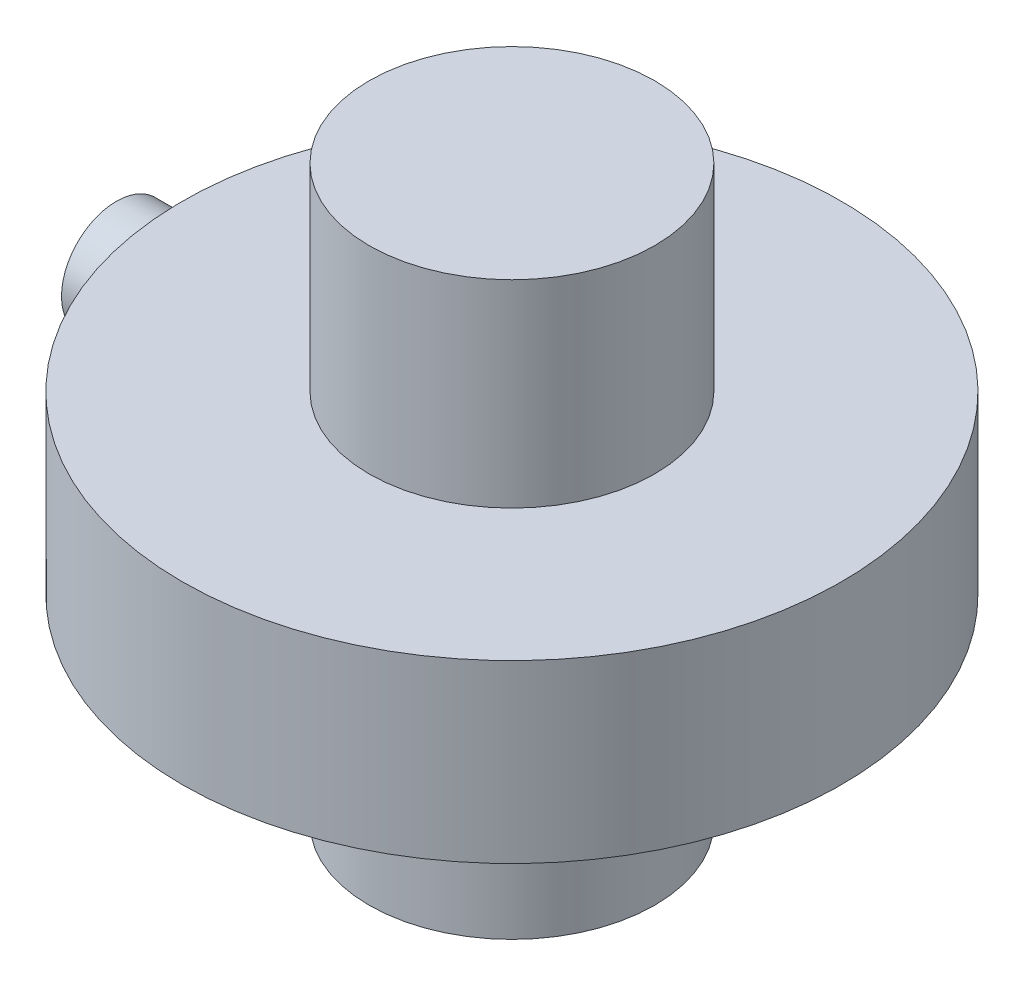
SolidWorks part; units mm, degrees
ref_plane "Front Plane" through (0, 0, 0) normal (0, 0, 1) x (1, 0, 0)
ref_plane "Top Plane" through (0, 0, 0) normal (0, 1, 0) x (1, 0, 0)
ref_plane "Right Plane" through (0, 0, 0) normal (1, 0, 0) x (0, 0, -1)
sketch "Sketch1" plane through (0, 0, 0) normal (1, 0, 0) x (0, 0, -1)
  circle A0 centre (0, 0) radius 5
  dimension "D1" = 10
extrude "Boss-Extrude1" add sketch "Sketch1" along normal blind 10
sketch "Sketch2" plane through (0, 0, 0) normal (0, 1, 0) x (1, 0, 0)
  circle A0 centre (36, 0) radius 30
  dimension "D2" = 60
  dimension "D1" = 36
extrude "Boss-Extrude2" add sketch "Sketch2" along normal mid plane 16
sketch "Sketch3" plane through (0, 0, 0) normal (0, 1, 0) x (1, 0, 0)
  circle A0 centre (36, 0) radius 13
  dimension "D1" = 26
extrude "Boss-Extrude3" add sketch "Sketch3" along normal mid plane 52
